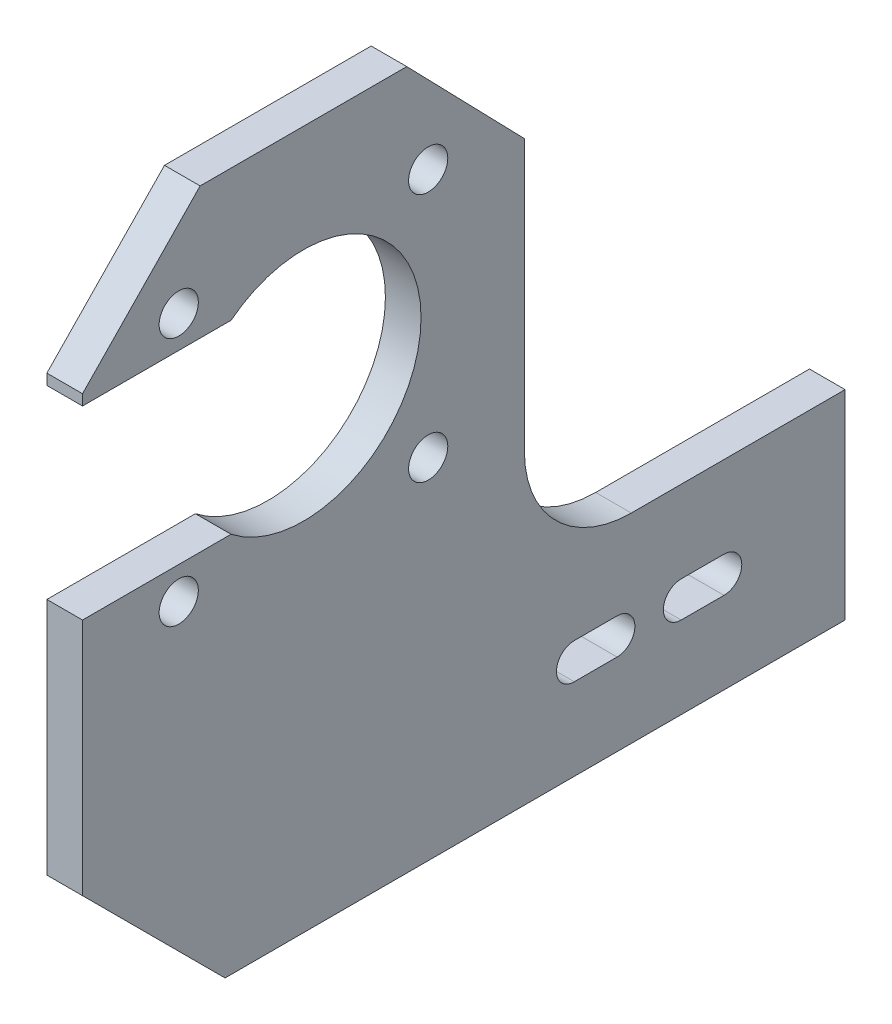
SolidWorks part; units mm, degrees
ref_plane "Plano frontal" through (0, 0, 0) normal (0, 0, 1) x (1, 0, 0)
ref_plane "Plano superior" through (0, 0, 0) normal (0, 1, 0) x (1, 0, 0)
ref_plane "Plano direito" through (0, 0, 0) normal (1, 0, 0) x (0, 0, -1)
sketch "Esboço2" plane through (0, 0, 0) normal (1, 0, 0) x (0, 0, -1)
  line L0 (0, 49) -> (16.5, 66)
  line L4 (62, 0) -> (62, 49)
  line L5 (16.5, 66) -> (45.5, 66)
  line L6 (45.5, 66) -> (62, 49)
  line L7 (31, 66) -> (31, 0) construction
  line L9 (62, 49) -> (0, 49) construction
  line L11 (0, 0) -> (0, -32)
  line L12 (0, -32) -> (107, -32)
  line L13 (107, -32) -> (107, -4)
  line L14 (107, -4) -> (62, -4)
  line L15 (62, -4) -> (62, 0)
  line L16 (0, 0) -> (62, 0) construction
  line L17 (69, -18) -> (75, -18) construction
  line L18 (69, -15.5) -> (75, -15.5)
  line L19 (69, -20.5) -> (75, -20.5)
  line L20 (84, -18) -> (90, -18) construction
  line L21 (84, -15.5) -> (90, -15.5)
  line L22 (84, -20.5) -> (90, -20.5)
  line L23 (0, 0) -> (0, 21.5)
  line L24 (0, 21.5) -> (20.8388, 21.5)
  line L25 (0, 49) -> (0, 47.5)
  line L26 (0, 47.5) -> (20.8388, 47.5)
  line L27 (0, 21.5) -> (0, 47.5) construction
  line L28 (31, 34.5) -> (0, 34.5) construction
  line L29 (13.5, 52) -> (48.5, 52) construction
  arc A1 (20.8388, 21.5) -> (20.8388, 47.5) centre (31, 34.5) ccw
  arc A2 (69, -15.5) -> (69, -20.5) centre (69, -18) ccw
  arc A3 (75, -20.5) -> (75, -15.5) centre (75, -18) ccw
  arc A4 (84, -15.5) -> (84, -20.5) centre (84, -18) ccw
  arc A5 (90, -20.5) -> (90, -15.5) centre (90, -18) ccw
  circle A14 centre (48.5, 52) radius 2.75
  circle A15 centre (13.5, 52) radius 2.75
  circle A16 centre (48.5, 17) radius 2.75
  circle A17 centre (13.5, 17) radius 2.75
  point P10 (72, -18)
  point P26 (87, -18)
  point P41 (31, 52)
  dimension "D5" = 33
  dimension "D2" = 49
  dimension "D6" = 17.5
  dimension "D11" = 2.5
  dimension "D15" = 13
  dimension "D18" = 5.5
  dimension "D1" = 66
  dimension "D3" = 62
  dimension "D4" = 29
  dimension "D7" = 28
  dimension "D8" = 107
  dimension "D9" = 32
  dimension "D10" = 14
  dimension "D12" = 20
  dimension "D13" = 15
  dimension "D14" = 6
  dimension "D16" = 34.5
  dimension "D17" = 17.5
extrude "Corpo" add sketch "Esboço2" against normal blind 5
fillet "Raio de Alívio de Tensão - R15" radius 15 1 edges at (-2.5, -4, -62)
chamfer "Chamfer1" distance 20 angle 45 1 edges at (-2.5, -32, 0)
